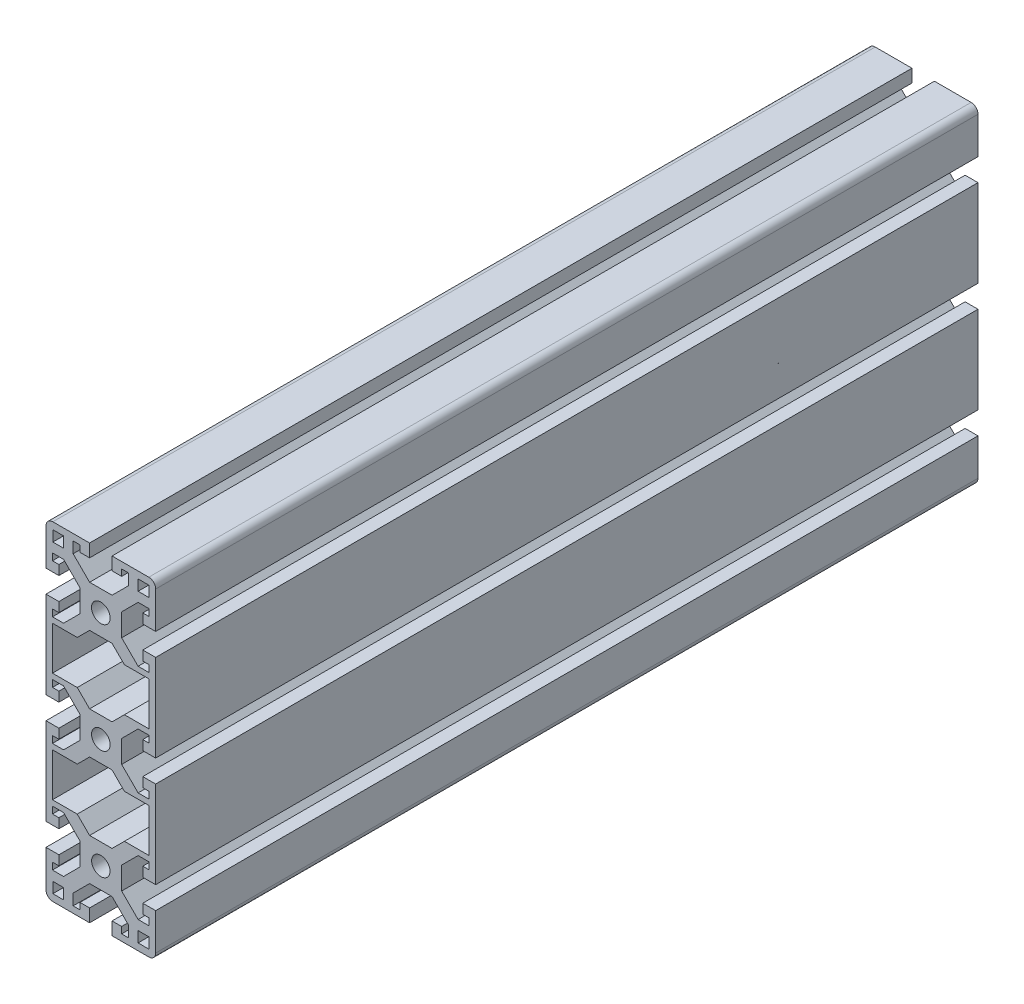
SolidWorks part; units mm, degrees
material "6063-T6"
ref_plane "Front Plane" through (0, 0, 0) normal (0, 0, 1) x (1, 0, 0)
ref_plane "Top Plane" through (0, 0, 0) normal (0, 1, 0) x (1, 0, 0)
ref_plane "Right Plane" through (0, 0, 0) normal (1, 0, 0) x (0, 0, -1)
sketch "Sketch1" plane through (0, 0, 0) normal (0, 1, 0) x (1, 0, 0)
  line L0 (0, -150) -> (0, 150)
  dimension "D1" = 300
other "40 series TS40-120LM(1)"
ref_plane "Plane1" through (0, 0, 150) normal (0, 0, -1) x (-1, 0, 0)
sketch "Sketch22" plane through (0, 0, 150) normal (0, 0, -1) x (-1, 0, 0)
  line L0 (15.3, -35.9) -> (20, -35.9)
  line L1 (3.35, 0) -> (7.6, 0) construction
  line L2 (7.6, 4.1) -> (7.6, -4.1)
  line L3 (7.6, -4.1) -> (13.6, -10.1)
  line L4 (13.6, -10.1) -> (17.65, -10.1)
  line L5 (17.65, -10.1) -> (17.65, -7.6)
  line L6 (17.65, -7.6) -> (15.3, -7.6)
  line L7 (15.3, -7.6) -> (15.3, -4.1)
  line L8 (15.3, -4.1) -> (20, -4.1)
  line L9 (20, -4.1) -> (20, -35.9)
  line L10 (0, -3.35) -> (0, -7.6) construction
  line L11 (-4.1, -7.6) -> (4.1, -7.6)
  line L12 (4.1, -7.6) -> (8.6, -12.1)
  line L13 (8.6, -12.1) -> (17.65, -12.1)
  line L14 (17.65, -12.1) -> (17.65, -27.9)
  line L15 (20, -20) -> (0, 0) construction
  line L16 (17.65, -20) -> (20, -20) construction
  line L17 (15.3, -32.4) -> (15.3, -35.9)
  line L18 (17.65, -32.4) -> (15.3, -32.4)
  line L19 (17.65, -29.9) -> (17.65, -32.4)
  line L20 (13.6, -29.9) -> (17.65, -29.9)
  line L21 (8.6, -27.9) -> (17.65, -27.9)
  line L22 (7.6, -35.9) -> (13.6, -29.9)
  line L23 (7.6, -44.1) -> (7.6, -35.9)
  line L24 (4.1, -32.4) -> (8.6, -27.9)
  line L25 (-4.1, -32.4) -> (4.1, -32.4)
  line L26 (3.35, -40) -> (7.6, -40) construction
  line L27 (15.3, -44.1) -> (20, -44.1)
  line L28 (15.3, -47.6) -> (15.3, -44.1)
  line L29 (17.65, -47.6) -> (15.3, -47.6)
  line L30 (17.65, -50.1) -> (17.65, -47.6)
  line L31 (13.6, -50.1) -> (17.65, -50.1)
  line L32 (7.6, -44.1) -> (13.6, -50.1)
  line L33 (0, -40) -> (19.2678, -59.2678) construction
  line L34 (20, -57.5) -> (20, -44.1)
  line L35 (17.5, -60) -> (4.1, -60)
  line L36 (4.1, -55.3) -> (4.1, -60)
  line L37 (7.6, -55.3) -> (4.1, -55.3)
  line L38 (7.6, -57.65) -> (7.6, -55.3)
  line L39 (10.1, -57.65) -> (7.6, -57.65)
  line L40 (10.1, -53.6) -> (10.1, -57.65)
  line L41 (4.1, -47.6) -> (10.1, -53.6)
  line L42 (4.1, -47.6) -> (-4.1, -47.6)
  line L43 (0, -40) -> (-19.2678, -59.2678) construction
  line L44 (-3.35, -40) -> (-7.6, -40) construction
  line L45 (-17.65, -20) -> (-20, -20) construction
  line L46 (-20, -20) -> (0, 0) construction
  line L47 (-3.35, 0) -> (-7.6, 0) construction
  line L48 (-4.1, -47.6) -> (-10.1, -53.6)
  line L49 (-10.1, -53.6) -> (-10.1, -57.65)
  line L50 (-10.1, -57.65) -> (-7.6, -57.65)
  line L51 (-7.6, -57.65) -> (-7.6, -55.3)
  line L52 (-7.6, -55.3) -> (-4.1, -55.3)
  line L53 (-4.1, -55.3) -> (-4.1, -60)
  line L54 (-17.5, -60) -> (-4.1, -60)
  line L55 (-20, -57.5) -> (-20, -44.1)
  line L56 (-7.6, -44.1) -> (-13.6, -50.1)
  line L57 (-13.6, -50.1) -> (-17.65, -50.1)
  line L58 (-17.65, -50.1) -> (-17.65, -47.6)
  line L59 (-17.65, -47.6) -> (-15.3, -47.6)
  line L60 (-15.3, -47.6) -> (-15.3, -44.1)
  line L61 (-15.3, -44.1) -> (-20, -44.1)
  line L62 (-4.1, -32.4) -> (-8.6, -27.9)
  line L63 (-7.6, -44.1) -> (-7.6, -35.9)
  line L64 (-7.6, -35.9) -> (-13.6, -29.9)
  line L65 (-8.6, -27.9) -> (-17.65, -27.9)
  line L66 (-13.6, -29.9) -> (-17.65, -29.9)
  line L67 (-17.65, -29.9) -> (-17.65, -32.4)
  line L68 (-17.65, -32.4) -> (-15.3, -32.4)
  line L69 (-15.3, -32.4) -> (-15.3, -35.9)
  line L70 (-17.65, -12.1) -> (-17.65, -27.9)
  line L71 (-8.6, -12.1) -> (-17.65, -12.1)
  line L72 (-4.1, -7.6) -> (-8.6, -12.1)
  line L73 (-20, -4.1) -> (-20, -35.9)
  line L74 (-15.3, -4.1) -> (-20, -4.1)
  line L75 (-15.3, -7.6) -> (-15.3, -4.1)
  line L76 (-17.65, -7.6) -> (-15.3, -7.6)
  line L77 (-17.65, -10.1) -> (-17.65, -7.6)
  line L78 (-13.6, -10.1) -> (-17.65, -10.1)
  line L79 (-7.6, -4.1) -> (-13.6, -10.1)
  line L80 (-7.6, 4.1) -> (-7.6, -4.1)
  line L81 (-15.3, -35.9) -> (-20, -35.9)
  line L82 (-20, 20) -> (0, 0) construction
  line L83 (-17.65, 20) -> (-20, 20) construction
  line L84 (-3.35, 40) -> (-7.6, 40) construction
  line L85 (0, 40) -> (-19.2678, 59.2678) construction
  line L86 (0, 40) -> (19.2678, 59.2678) construction
  line L87 (3.35, 40) -> (7.6, 40) construction
  line L88 (17.65, 20) -> (20, 20) construction
  line L89 (20, 20) -> (0, 0) construction
  line L90 (0, 3.35) -> (0, 7.6) construction
  line L91 (-15.3, 35.9) -> (-20, 35.9)
  line L92 (-7.6, 4.1) -> (-13.6, 10.1)
  line L93 (-13.6, 10.1) -> (-17.65, 10.1)
  line L94 (-17.65, 10.1) -> (-17.65, 7.6)
  line L95 (-17.65, 7.6) -> (-15.3, 7.6)
  line L96 (-15.3, 7.6) -> (-15.3, 4.1)
  line L97 (-15.3, 4.1) -> (-20, 4.1)
  line L98 (-20, 4.1) -> (-20, 35.9)
  line L99 (-4.1, 7.6) -> (-8.6, 12.1)
  line L100 (-8.6, 12.1) -> (-17.65, 12.1)
  line L101 (-17.65, 12.1) -> (-17.65, 27.9)
  line L102 (-15.3, 32.4) -> (-15.3, 35.9)
  line L103 (-17.65, 32.4) -> (-15.3, 32.4)
  line L104 (-17.65, 29.9) -> (-17.65, 32.4)
  line L105 (-13.6, 29.9) -> (-17.65, 29.9)
  line L106 (-8.6, 27.9) -> (-17.65, 27.9)
  line L107 (-7.6, 35.9) -> (-13.6, 29.9)
  line L108 (-7.6, 44.1) -> (-7.6, 35.9)
  line L109 (-4.1, 32.4) -> (-8.6, 27.9)
  line L110 (-15.3, 44.1) -> (-20, 44.1)
  line L111 (-15.3, 47.6) -> (-15.3, 44.1)
  line L112 (-17.65, 47.6) -> (-15.3, 47.6)
  line L113 (-17.65, 50.1) -> (-17.65, 47.6)
  line L114 (-13.6, 50.1) -> (-17.65, 50.1)
  line L115 (-7.6, 44.1) -> (-13.6, 50.1)
  line L116 (-20, 57.5) -> (-20, 44.1)
  line L117 (-17.5, 60) -> (-4.1, 60)
  line L118 (-4.1, 55.3) -> (-4.1, 60)
  line L119 (-7.6, 55.3) -> (-4.1, 55.3)
  line L120 (-7.6, 57.65) -> (-7.6, 55.3)
  line L121 (-10.1, 57.65) -> (-7.6, 57.65)
  line L122 (-10.1, 53.6) -> (-10.1, 57.65)
  line L123 (-4.1, 47.6) -> (-10.1, 53.6)
  line L124 (4.1, 47.6) -> (-4.1, 47.6)
  line L125 (4.1, 47.6) -> (10.1, 53.6)
  line L126 (10.1, 53.6) -> (10.1, 57.65)
  line L127 (10.1, 57.65) -> (7.6, 57.65)
  line L128 (7.6, 57.65) -> (7.6, 55.3)
  line L129 (7.6, 55.3) -> (4.1, 55.3)
  line L130 (4.1, 55.3) -> (4.1, 60)
  line L131 (17.5, 60) -> (4.1, 60)
  line L132 (20, 57.5) -> (20, 44.1)
  line L133 (7.6, 44.1) -> (13.6, 50.1)
  line L134 (13.6, 50.1) -> (17.65, 50.1)
  line L135 (17.65, 50.1) -> (17.65, 47.6)
  line L136 (17.65, 47.6) -> (15.3, 47.6)
  line L137 (15.3, 47.6) -> (15.3, 44.1)
  line L138 (15.3, 44.1) -> (20, 44.1)
  line L139 (-4.1, 32.4) -> (4.1, 32.4)
  line L140 (4.1, 32.4) -> (8.6, 27.9)
  line L141 (7.6, 44.1) -> (7.6, 35.9)
  line L142 (7.6, 35.9) -> (13.6, 29.9)
  line L143 (8.6, 27.9) -> (17.65, 27.9)
  line L144 (13.6, 29.9) -> (17.65, 29.9)
  line L145 (17.65, 29.9) -> (17.65, 32.4)
  line L146 (17.65, 32.4) -> (15.3, 32.4)
  line L147 (15.3, 32.4) -> (15.3, 35.9)
  line L148 (17.65, 12.1) -> (17.65, 27.9)
  line L149 (8.6, 12.1) -> (17.65, 12.1)
  line L150 (4.1, 7.6) -> (8.6, 12.1)
  line L151 (-4.1, 7.6) -> (4.1, 7.6)
  line L152 (20, 4.1) -> (20, 35.9)
  line L153 (15.3, 4.1) -> (20, 4.1)
  line L154 (15.3, 7.6) -> (15.3, 4.1)
  line L155 (17.65, 7.6) -> (15.3, 7.6)
  line L156 (17.65, 10.1) -> (17.65, 7.6)
  line L157 (13.6, 10.1) -> (17.65, 10.1)
  line L158 (7.6, 4.1) -> (13.6, 10.1)
  line L159 (15.3, 35.9) -> (20, 35.9)
  line L161 (13.6, -53.6) -> (17.5, -53.6)
  line L162 (13.6, -53.6) -> (13.6, -57.5)
  line L163 (13.6, -57.5) -> (17.5, -57.5)
  line L164 (17.5, -53.6) -> (17.5, -57.5)
  line L165 (-17.5, -57.5) -> (-13.6, -57.5)
  line L166 (-17.5, -57.5) -> (-17.5, -53.6)
  line L167 (-17.5, -53.6) -> (-13.6, -53.6)
  line L168 (-13.6, -57.5) -> (-13.6, -53.6)
  line L169 (-17.5, 57.5) -> (-13.6, 57.5)
  line L170 (-17.5, 57.5) -> (-17.5, 53.6)
  line L171 (-17.5, 53.6) -> (-13.6, 53.6)
  line L172 (-13.6, 57.5) -> (-13.6, 53.6)
  line L173 (17.5, 57.5) -> (13.6, 57.5)
  line L174 (17.5, 57.5) -> (17.5, 53.6)
  line L175 (17.5, 53.6) -> (13.6, 53.6)
  line L176 (13.6, 57.5) -> (13.6, 53.6)
  arc A0 (0, -43.35) -> (0, -36.65) centre (0, -40) ccw
  arc A1 (3.35, 0) -> (-3.35, 0) centre (0, 0) cw
  arc A2 (17.5, -60) -> (20, -57.5) centre (17.5, -57.5) ccw
  arc A3 (-17.5, -60) -> (-20, -57.5) centre (-17.5, -57.5) cw
  arc A4 (0, -43.35) -> (0, -36.65) centre (0, -40) cw
  arc A5 (0, 43.35) -> (0, 36.65) centre (0, 40) ccw
  arc A6 (-17.5, 60) -> (-20, 57.5) centre (-17.5, 57.5) ccw
  arc A7 (17.5, 60) -> (20, 57.5) centre (17.5, 57.5) cw
  arc A8 (3.35, 0) -> (-3.35, 0) centre (0, 0) ccw
  arc A9 (0, 43.35) -> (0, 36.65) centre (0, 40) cw
  point P19 (17.65, -4.1)
  point P65 (0, -47.6)
  point P79 (0, -32.4)
  point P196 (0, 32.4)
  point P197 (0, 47.6)
  point P201 (20, -60)
  point P202 (-20, -60)
  point P203 (20, -40)
  point P204 (-20, -40)
  point P205 (20, -20)
  point P206 (0, -60)
  point P207 (0, -40)
  point P208 (-20, -20)
  point P209 (-20, 0)
  point P210 (20, 0)
  point P211 (20, 40)
  point P212 (0, 0)
  point P213 (-20, 20)
  point P214 (20, 20)
  point P215 (-20, 40)
  point P216 (0, 40)
  point P217 (20, 60)
  point P218 (0, 60)
  point P219 (-20, 60)
  point P220 (0, 20)
  point P221 (0, -20)
  point P222 (0, 0)
  dimension "D2" = 4.1
  dimension "D4" = 12.4
  dimension "D9" = 2.5
  dimension "D3" = 3.35
  dimension "D5" = 20
  dimension "D10" = 20
  dimension "D6" = 10.1
  dimension "D8" = 2
  dimension "D11" = 2.5
  dimension "D7" = 4.7
hole_wizard "M8x1.25 Tapped Hole1" positions "Sketch3" profile "Sketch4" tap size "M8x1.25" standard "ANSI Metric"
sketch "Sketch3" plane through (0, 0, 150) normal (0, 0, 1) x (1, 0, 0)
  point P0 (0, 0)
  point P3 (0, 40)
  point P14 (0, 0)
sketch "Sketch4" plane through (0, 0, 150) normal (1, 0, 0) x (0, -1, 0)
  line L0 (0, 0) -> (0, 32.0429)
  line L1 (0, 32.0429) -> (3.4, 30)
  line L2 (3.4, 30) -> (3.4, 0)
  line L5 (3.4, 0) -> (0, 0)
  line L10 (0, 32.0429) -> (-3.4, 30) construction
  line L11 (0, -6.35) -> (0, 107.95) construction
  dimension "Tap Drill Dia." = 6.8
  dimension "Tap Drill Depth" = 30
  dimension "Drill Angle" = 118
cosmetic thread "Hole Thread1" parameters "D1"=25, "D2"=8
cosmetic thread "Hole Thread2" parameters "D1"=25, "D2"=8
mirror "Mirror1" about plane through (0, 0, 0) normal (0, 0, 1) of "M8x1.25 Tapped Hole1"
cosmetic thread "Hole Thread3" parameters "D1"=25, "D2"=8
cosmetic thread "Hole Thread4" parameters "D1"=25, "D2"=8
